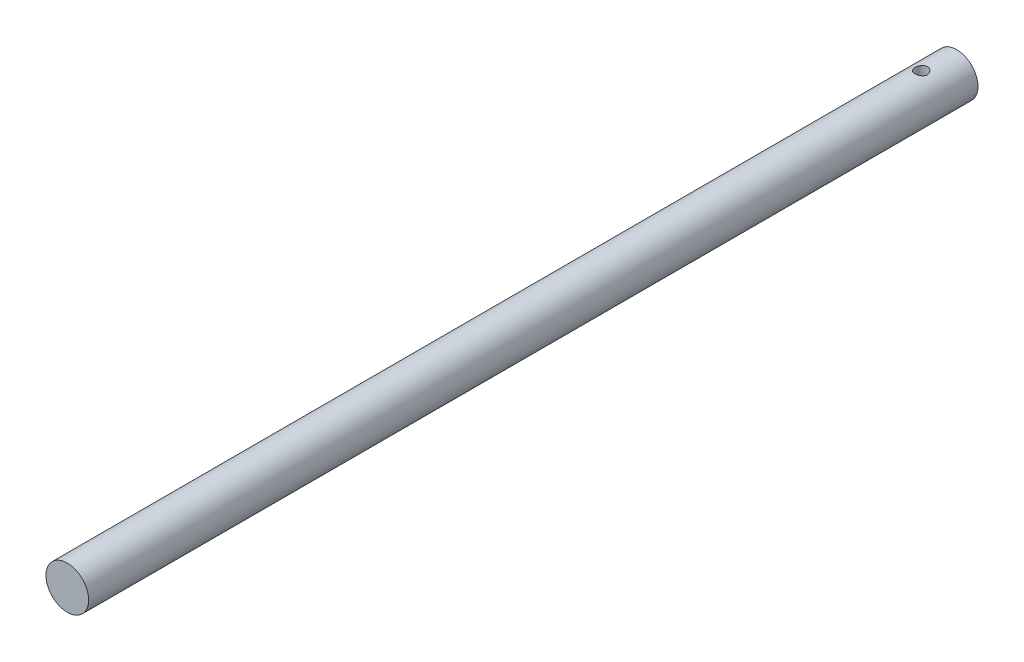
SolidWorks part; units mm, degrees
ref_plane "Front Plane" through (0, 0, 0) normal (0, 0, 1) x (1, 0, 0)
ref_plane "Top Plane" through (0, 0, 0) normal (0, 1, 0) x (1, 0, 0)
ref_plane "Right Plane" through (0, 0, 0) normal (1, 0, 0) x (0, 0, -1)
sketch "Sketch1" plane through (0, 0, 0) normal (0, 0, 1) x (1, 0, 0)
  circle A0 centre (0, 0) radius 6
  dimension "D1" = 12
extrude "Boss-Extrude1" add sketch "Sketch1" along normal blind 250
sketch "Sketch2" plane through (0, 0, 0) normal (0, 1, 0) x (1, 0, 0)
  line L0 (0, 0) -> (0, -10)
  circle A0 centre (0, -10) radius 1.75
  dimension "D2" = 3.5
  dimension "D1" = 10
extrude "Cut-Extrude1" cut sketch "Sketch2" against normal mid plane 36
